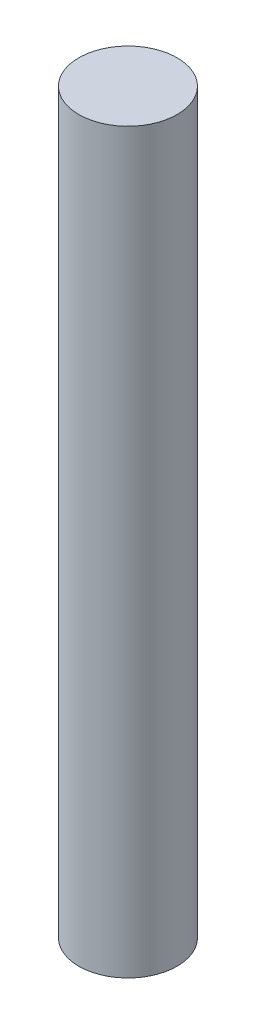
SolidWorks part; units mm, degrees
material "ASTM A36 Steel"
ref_plane "Front Plane" through (0, 0, 0) normal (0, 0, 1) x (1, 0, 0)
ref_plane "Top Plane" through (0, 0, 0) normal (0, 1, 0) x (1, 0, 0)
ref_plane "Right Plane" through (0, 0, 0) normal (1, 0, 0) x (0, 0, -1)
sketch "Sketch2" plane through (0, 0, 0) normal (0, 1, 0) x (1, 0, 0)
  circle A0 centre (0, 0) radius 8
  dimension "D1" = 16
extrude "Boss-Extrude1" add sketch "Sketch2" along normal mid plane 120
